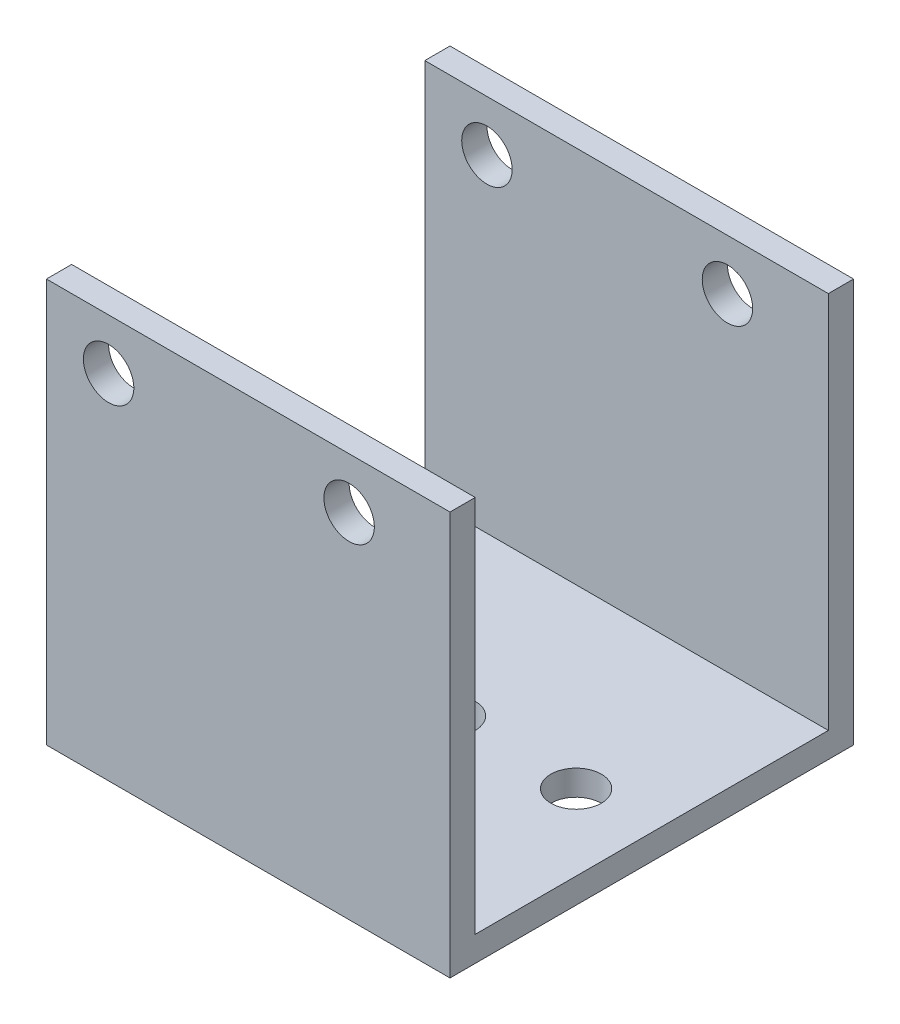
SolidWorks part; units mm, degrees
material "6061 Alloy"
ref_plane "Front Plane" through (0, 0, 0) normal (0, 0, 1) x (1, 0, 0)
ref_plane "Top Plane" through (0, 0, 0) normal (0, 1, 0) x (1, 0, 0)
ref_plane "Right Plane" through (0, 0, 0) normal (1, 0, 0) x (0, 0, -1)
sketch "Sketch1" plane through (0, 0, 0) normal (1, 0, 0) x (0, 0, -1)
  line L0 (-29.2659, 19.0698) -> (-29.2659, -31.7302)
  line L1 (-29.2659, -31.7302) -> (21.5341, -31.7302)
  line L2 (21.5341, -31.7302) -> (21.5341, 19.0698)
  line L3 (-26.0909, 19.0698) -> (-26.0909, -28.5552)
  line L4 (-26.0909, -28.5552) -> (18.3591, -28.5552)
  line L5 (18.3591, -28.5552) -> (18.3591, 19.0698)
  line L6 (-29.2659, 19.0698) -> (-26.0909, 19.0698)
  line L7 (18.3591, 19.0698) -> (21.5341, 19.0698)
  dimension "D2" = 50.8
  dimension "D3" = 50.8
  dimension "D4" = 50.8
  dimension "D1" = 3.175
extrude "Boss-Extrude1" add sketch "Sketch1" along normal blind 50.8
sketch "Sketch2" plane through (0, 0, -21.5341) normal (0, 0, -1) x (-1, 0, 0)
  circle A0 centre (-38.1, 12.6805) radius 3.175
  circle A1 centre (-7.8232, 12.6805) radius 3.175
  circle A2 centre (-7.8232, 12.6805) radius 3.175 construction
  circle A3 centre (-38.1, 12.6805) radius 3.175 construction
  dimension "D1" = 6.35
extrude "Cut-Extrude1" cut sketch "Sketch2" against normal blind 50.8
sketch "Sketch6" plane through (0, -31.7302, 0) normal (0, -1, 0) x (1, 0, 0)
  line L0 (50.8, 3.8659) -> (0, 3.8659) construction
  line L1 (50.8, 29.2659) -> (50.8, -21.5341) construction
  line L2 (0, 29.2659) -> (0, -21.5341) construction
  circle A0 centre (41.275, 3.8659) radius 3.175
  circle A1 centre (25.4, 3.8659) radius 3.175
  circle A2 centre (9.525, 3.8659) radius 3.175
  dimension "D1" = 6.35
  dimension "D2" = 9.525
  dimension "D3" = 25.4
  dimension "D4" = 41.275
extrude "Cut-Extrude2" cut sketch "Sketch6" against normal blind 50.8
